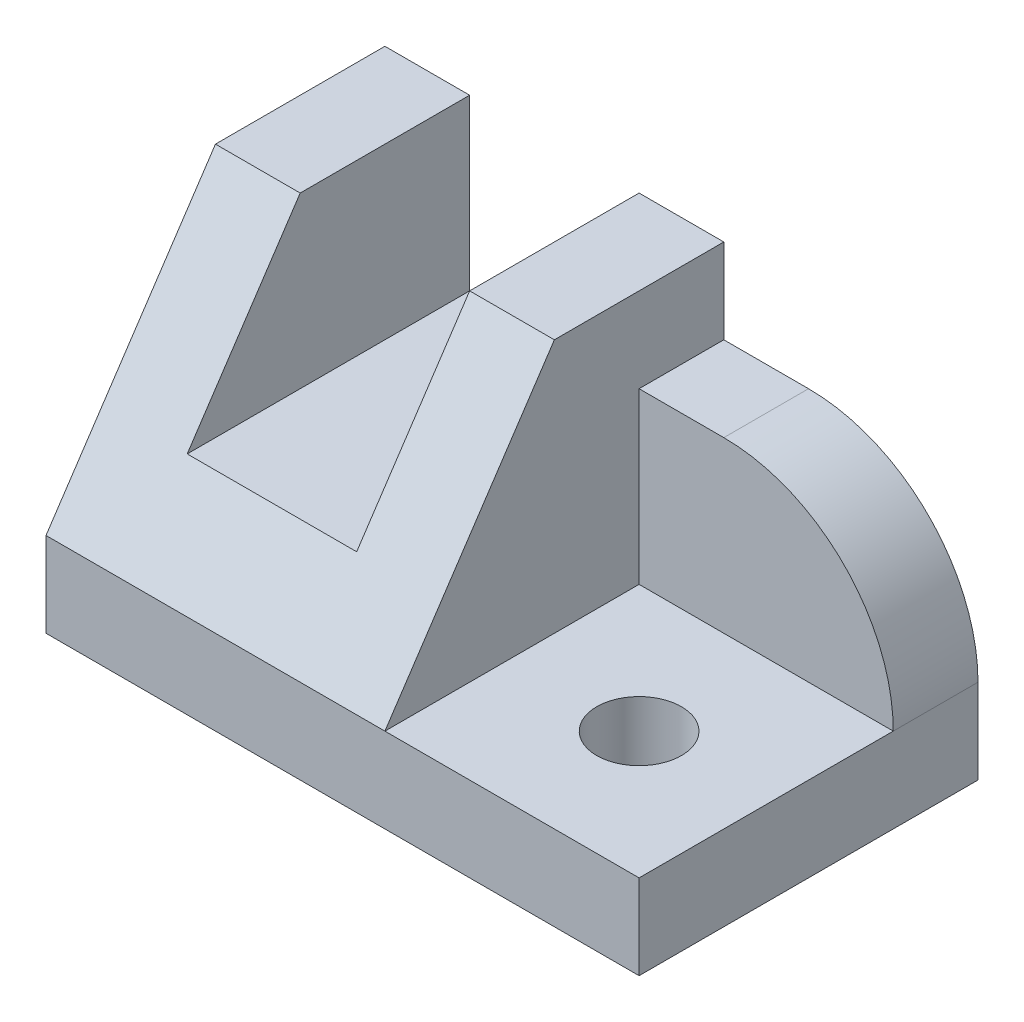
SolidWorks part; units mm, degrees
ref_plane "Front Plane" through (0, 0, 0) normal (0, 0, 1) x (1, 0, 0)
ref_plane "Top Plane" through (0, 0, 0) normal (0, 1, 0) x (1, 0, 0)
ref_plane "Right Plane" through (0, 0, 0) normal (1, 0, 0) x (0, 0, -1)
sketch "Sketch1" plane through (0, 0, 0) normal (0, 0, 1) x (1, 0, 0)
  line L0 (0, 20) -> (-10, 20)
  line L1 (-10, 20) -> (-10, 30)
  line L2 (-10, 30) -> (-20, 30)
  line L3 (-20, 30) -> (-20, 10)
  line L4 (-20, 10) -> (-40, 10)
  line L5 (-40, 10) -> (-40, 30)
  line L6 (-40, 30) -> (-50, 30)
  line L7 (-50, 30) -> (-50, -10)
  line L8 (-50, -10) -> (20, -10)
  line L9 (20, -10) -> (20, 0)
  arc A0 (20, 0) -> (0, 20) centre (0, 0) ccw
  dimension "D1" = 40
  dimension "D2" = 10
  dimension "D3" = 70
  dimension "D4" = 40
  dimension "D5" = 10
  dimension "D6" = 20
  dimension "D7" = 20
  dimension "D8" = 20
  dimension "D9" = 10
extrude "Boss-Extrude1" add sketch "Sketch1" along normal blind 40
sketch "Sketch2" plane through (-50, 0, 0) normal (-1, 0, 0) x (0, 0, 1)
  line L0 (20, 30) -> (40, 0)
  line L1 (40, 30) -> (0, 30) construction
  line L2 (40, 30) -> (40, -10) construction
  line L3 (40, 0) -> (40, 30)
  line L4 (40, 30) -> (20, 30)
  dimension "D1" = 30
  dimension "D2" = 20
extrude "Cut-Extrude1" cut sketch "Sketch2" against normal blind 91
sketch "Sketch3" plane through (0, 20, 0) normal (0, 1, 0) x (1, 0, 0)
  line L0 (-10, -20) -> (-10, 0) construction
  line L1 (-10, -10) -> (20, -10)
  line L2 (-10, -10) -> (-10, -40)
  line L3 (-10, -40) -> (20, -40)
  line L4 (20, -10) -> (20, -40)
  line L5 (20, 0) -> (0, 0) construction
  dimension "D1" = 10
extrude "Cut-Extrude2" cut sketch "Sketch3" against normal blind 20
sketch "Sketch4" plane through (0, 0, 0) normal (0, 1, 0) x (1, 0, 0)
  line L0 (20, -40) -> (20, -10) construction
  line L1 (-10, -40) -> (20, -40) construction
  circle A0 centre (5, -25) radius 5
  dimension "D3" = 10
  dimension "D1" = 15
  dimension "D2" = 15
extrude "Cut-Extrude3" cut sketch "Sketch4" against normal blind 20 contours A0
